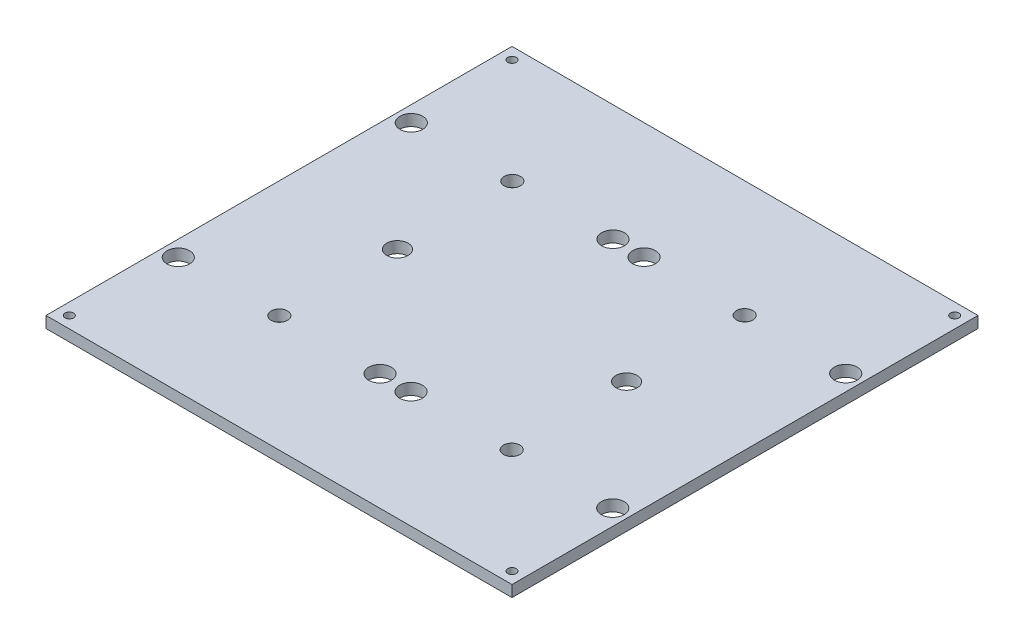
SolidWorks part; units mm, degrees
ref_plane "Front Plane" through (0, 0, 0) normal (0, 0, 1) x (1, 0, 0)
ref_plane "Top Plane" through (0, 0, 0) normal (0, 1, 0) x (1, 0, 0)
ref_plane "Right Plane" through (0, 0, 0) normal (1, 0, 0) x (0, 0, -1)
sketch "Sketch1" plane through (0, 0, 0) normal (0, 1, 0) x (1, 0, 0)
  line L0 (-30, 0) -> (0, 0) construction
  line L1 (30, 30) -> (-30, 30)
  line L2 (30, 30) -> (30, -30)
  line L3 (30, -30) -> (-30, -30)
  line L4 (-30, 30) -> (-30, -30)
  line L5 (30, 30) -> (-30, -30) construction
  line L6 (30, -30) -> (-30, 30) construction
  line L7 (0, 0) -> (0, 30) construction
  circle A0 centre (-28.5, 28.5) radius 0.55
  circle A1 centre (-27.968, 15) radius 1.465
  circle A2 centre (-14.75, 0) radius 1.375
  circle A3 centre (-14.96, 15) radius 1.055
  circle A4 centre (-2, 15) radius 1.465
  circle A5 centre (2, 15) radius 1.465
  circle A6 centre (14.96, 15) radius 1.055
  circle A7 centre (14.75, 0) radius 1.375
  circle A8 centre (27.968, 15) radius 1.465
  circle A9 centre (28.5, 28.5) radius 0.55
  circle A10 centre (28.5, -28.5) radius 0.55
  circle A11 centre (27.968, -15) radius 1.465
  circle A12 centre (14.96, -15) radius 1.055
  circle A13 centre (2, -15) radius 1.465
  circle A14 centre (-2, -15) radius 1.465
  circle A15 centre (-14.96, -15) radius 1.055
  circle A16 centre (-27.968, -15) radius 1.465
  circle A17 centre (-28.5, -28.5) radius 0.55
  point P0 (0, 0)
  dimension "D1" = 2.93
  dimension "D2" = 1.1
  dimension "D3" = 2.11
  dimension "D4" = 2.75
  dimension "D5" = 1.5
  dimension "D6" = 2.032
  dimension "D7" = 15.04
  dimension "D8" = 28
  dimension "D9" = 15.25
  dimension "D10" = 1.5
  dimension "D11" = 15
  dimension "D12" = 30
  dimension "D13" = 60
  dimension "D14" = 60
extrude "Boss-Extrude1" add sketch "Sketch1" along normal blind 1.46
